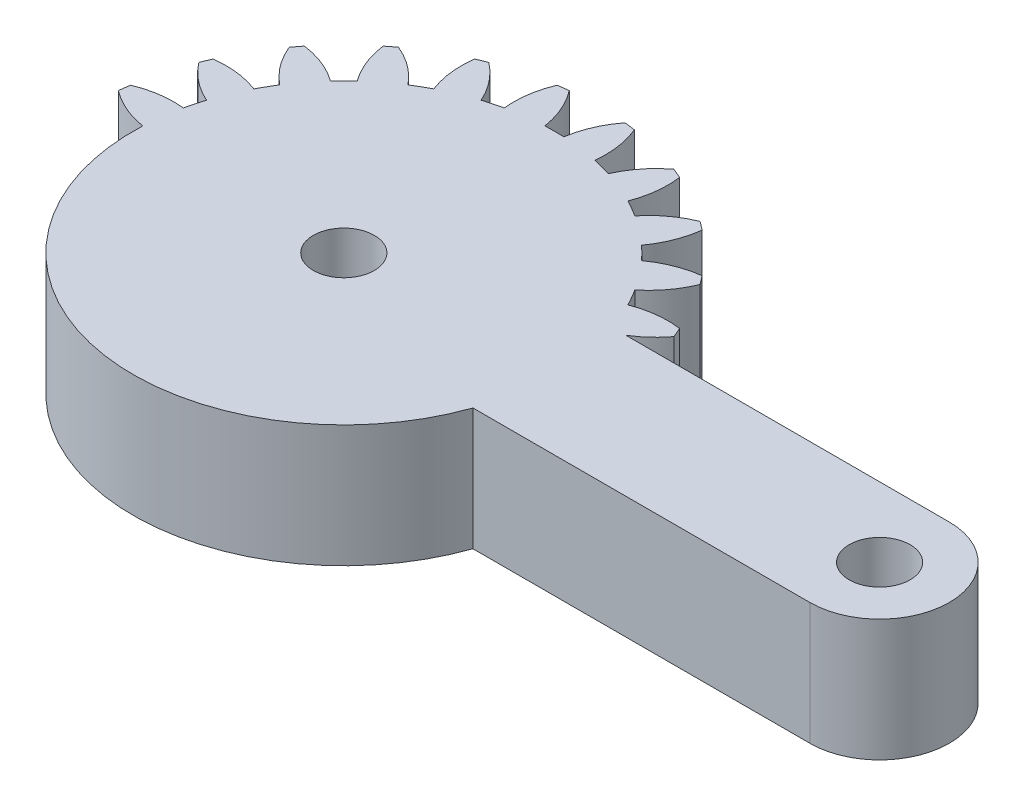
SolidWorks part; units mm, degrees
ref_plane "Front Plane" through (0, 0, 0) normal (0, 0, 1) x (1, 0, 0)
ref_plane "Top Plane" through (0, 0, 0) normal (0, 1, 0) x (1, 0, 0)
ref_plane "Right Plane" through (0, 0, 0) normal (1, 0, 0) x (0, 0, -1)
ref_plane "Plane1" through (0, 4, 0) normal (0, 1, 0) x (1, 0, 0)
sketch "Sketch1" plane through (0, 4, 0) normal (0, 1, 0) x (1, 0, 0)
  line L0 (1.3057, -4) -> (20.6437, -4)
  line L1 (20.6437, 4) -> (2.0816, 4)
  arc A0 (-24.5622, 2.2179) -> (-24.6437, 1.5991) centre (-10.1063, 0) ccw
  arc A1 (-24.6437, 1.5991) -> (-22.1869, 0.5427) centre (-21.3486, 5.8773) ccw
  arc A2 (-22.1869, 0.5427) -> (1.3057, -4) centre (-10.1063, 0) ccw
  arc A3 (20.6437, -4) -> (20.6437, 4) centre (20.6437, 0) ccw
  arc A4 (2.0816, 4) -> (3.5217, 5.3071) centre (-0.7683, 8.5867) ccw
  arc A5 (3.5217, 5.3071) -> (3.2829, 5.8838) centre (-10.1063, 0) ccw
  arc A6 (3.2829, 5.8838) -> (0.6271, 5.5703) centre (2.5684, 0.5313) ccw
  arc A7 (0.6271, 5.5703) -> (0.0844, 6.5103) centre (-10.1063, 0) ccw
  arc A8 (0.0844, 6.5103) -> (1.6838, 8.6535) centre (-3.3089, 10.711) ccw
  arc A9 (1.6838, 8.6535) -> (1.3038, 9.1487) centre (-10.1063, 0) ccw
  arc A10 (1.3038, 9.1487) -> (-1.1803, 8.1585) centre (1.999, 3.7936) ccw
  arc A11 (-1.1803, 8.1585) -> (-1.9479, 8.926) centre (-10.1063, 0) ccw
  arc A12 (-1.9479, 8.926) -> (-0.9576, 11.4102) centre (-6.3127, 12.1053) ccw
  arc A13 (-0.9576, 11.4102) -> (-1.4528, 11.7901) centre (-10.1063, 0) ccw
  arc A14 (-1.4528, 11.7901) -> (-3.596, 10.1907) centre (0.6046, 6.7975) ccw
  arc A15 (-3.596, 10.1907) -> (-4.5361, 10.7334) centre (-10.1063, 0) ccw
  arc A16 (-4.5361, 10.7334) -> (-4.2225, 13.3892) centre (-9.5751, 12.6747) ccw
  arc A17 (-4.2225, 13.3892) -> (-4.7992, 13.6281) centre (-10.1063, 0) ccw
  arc A18 (-4.7992, 13.6281) -> (-6.4554, 11.5285) centre (-1.5196, 9.3381) ccw
  arc A19 (-6.4554, 11.5285) -> (-7.5039, 11.8094) centre (-10.1063, 0) ccw
  arc A20 (-7.5039, 11.8094) -> (-7.8884, 14.4558) centre (-12.8736, 12.3803) ccw
  arc A21 (-7.8884, 14.4558) -> (-8.5072, 14.5373) centre (-10.1063, 0) ccw
  arc A22 (-8.5072, 14.5373) -> (-9.5636, 12.0806) centre (-4.2291, 11.2423) ccw
  arc A23 (-9.5636, 12.0806) -> (-10.6491, 12.0806) centre (-10.1063, 0) ccw
  arc A24 (-10.6491, 12.0806) -> (-11.7054, 14.5373) centre (-15.9836, 11.2423) ccw
  arc A25 (-11.7054, 14.5373) -> (-12.3243, 14.4558) centre (-10.1063, 0) ccw
  arc A26 (-12.3243, 14.4558) -> (-12.7088, 11.8094) centre (-7.3391, 12.3803) ccw
  arc A27 (-12.7088, 11.8094) -> (-13.7573, 11.5285) centre (-10.1063, 0) ccw
  arc A28 (-13.7573, 11.5285) -> (-15.4135, 13.6281) centre (-18.6931, 9.3381) ccw
  arc A29 (-15.4135, 13.6281) -> (-15.9901, 13.3892) centre (-10.1063, 0) ccw
  arc A30 (-15.9901, 13.3892) -> (-15.6766, 10.7334) centre (-10.6376, 12.6747) ccw
  arc A31 (-15.6766, 10.7334) -> (-16.6166, 10.1907) centre (-10.1063, 0) ccw
  arc A32 (-16.6166, 10.1907) -> (-18.7599, 11.7901) centre (-20.8173, 6.7975) ccw
  arc A33 (-18.7599, 11.7901) -> (-19.255, 11.4102) centre (-10.1063, 0) ccw
  arc A34 (-19.255, 11.4102) -> (-18.2648, 8.926) centre (-13.9, 12.1053) ccw
  arc A35 (-18.2648, 8.926) -> (-19.0324, 8.1585) centre (-10.1063, 0) ccw
  arc A36 (-19.0324, 8.1585) -> (-21.5165, 9.1487) centre (-22.2117, 3.7936) ccw
  arc A37 (-21.5165, 9.1487) -> (-21.8965, 8.6535) centre (-10.1063, 0) ccw
  arc A38 (-21.8965, 8.6535) -> (-20.2971, 6.5103) centre (-16.9038, 10.711) ccw
  arc A39 (-20.2971, 6.5103) -> (-20.8398, 5.5703) centre (-10.1063, 0) ccw
  arc A40 (-20.8398, 5.5703) -> (-23.4956, 5.8838) centre (-22.7811, 0.5313) ccw
  arc A41 (-23.4956, 5.8838) -> (-23.7344, 5.3071) centre (-10.1063, 0) ccw
  arc A42 (-23.7344, 5.3071) -> (-21.6348, 3.6509) centre (-19.4444, 8.5867) ccw
  arc A43 (-21.6348, 3.6509) -> (-21.9157, 2.6025) centre (-10.1063, 0) ccw
  arc A44 (-21.9157, 2.6025) -> (-24.5622, 2.2179) centre (-22.4867, -2.7673) ccw
  circle A45 centre (20.6437, 0) radius 1.75
  circle A46 centre (-10.1063, 0) radius 1.75
  dimension "D1" = 3.5
  dimension "D2" = 3.5
  dimension "D4" = 5.4
  dimension "D5" = 14.625
  dimension "D6" = 4
  dimension "D7" = 5.4
  dimension "D8" = 12.0927
  dimension "D9" = 5.4
  dimension "D10" = 0.0844
  dimension "D11" = 5.4
  dimension "D12" = 0.6046
  dimension "D13" = 5.4
  dimension "D14" = 0.6271
  dimension "D15" = 5.4
  dimension "D16" = 1.3038
  dimension "D17" = 5.4
  dimension "D18" = 1.3057
  dimension "D19" = 5.4
  dimension "D20" = 1.6838
  dimension "D21" = 5.4
  dimension "D22" = 1.999
  dimension "D23" = 5.4
  dimension "D24" = 2.0816
  dimension "D25" = 5.4
  dimension "D26" = 2.5684
  dimension "D27" = 5.4
  dimension "D28" = 3.2829
  dimension "D29" = 5.4
  dimension "D30" = 3.5217
  dimension "D31" = 5.4
  dimension "D32" = 20.6437
  dimension "D33" = 5.4
  dimension "D34" = 0.9576
  dimension "D35" = 5.4
  dimension "D36" = 1.4528
  dimension "D37" = 5.4
  dimension "D38" = 1.5196
  dimension "D39" = 5.4
  dimension "D40" = 1.9479
  dimension "D41" = 5.4
  dimension "D42" = 4.2225
  dimension "D43" = 5.4
  dimension "D44" = 4.2291
  dimension "D45" = 5.4
  dimension "D46" = 4.5361
  dimension "D47" = 5.4
  dimension "D48" = 4.7992
  dimension "D49" = 7.3391
  dimension "D50" = 7.5039
  dimension "D51" = 7.8884
  dimension "D52" = 8.5072
  dimension "D53" = 10.6376
  dimension "D54" = 10.6491
  dimension "D55" = 11.7054
  dimension "D56" = 12.3243
  dimension "D57" = 13.7573
  dimension "D58" = 13.9
  dimension "D59" = 15.4135
  dimension "D60" = 15.6766
  dimension "D61" = 16.6166
  dimension "D62" = 16.9038
  dimension "D63" = 18.2648
  dimension "D64" = 18.7599
  dimension "D65" = 19.0324
  dimension "D66" = 19.4444
  dimension "D67" = 20.2971
  dimension "D68" = 20.8398
  dimension "D69" = 21.3486
  dimension "D70" = 21.5165
  dimension "D71" = 21.6348
  dimension "D72" = 21.9157
  dimension "D73" = 22.1869
  dimension "D74" = 22.4867
  dimension "D75" = 22.7811
  dimension "D76" = 0.5313
extrude "Boss-Extrude1" add sketch "Sketch1" against normal blind 7
